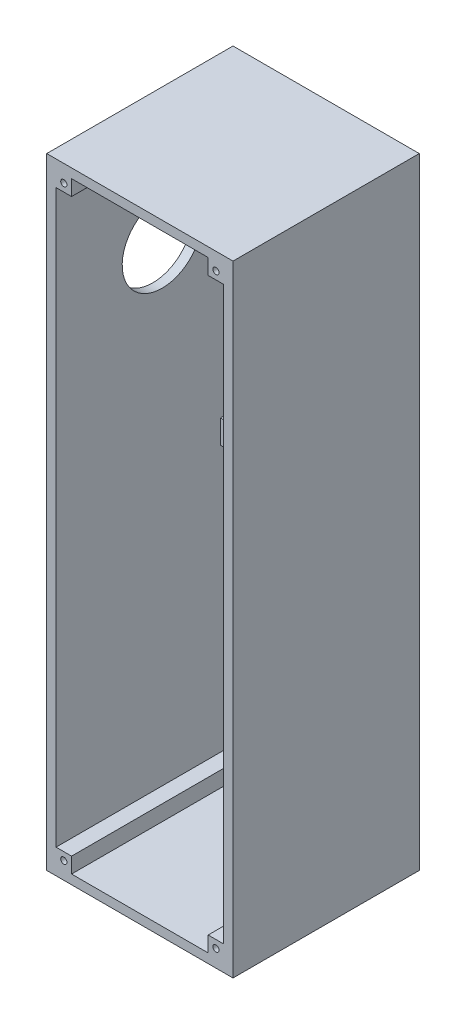
SolidWorks part; units mm, degrees
ref_plane "Płaszczyzna przednia" through (0, 0, 0) normal (0, 0, 1) x (1, 0, 0)
ref_plane "Płaszczyzna górna" through (0, 0, 0) normal (0, 1, 0) x (1, 0, 0)
ref_plane "Płaszczyzna prawa" through (0, 0, 0) normal (1, 0, 0) x (0, 0, -1)
sketch "Szkic1" plane through (0, 0, 0) normal (0, 1, 0) x (1, 0, 0)
  line L1 (0, 0) -> (60, 0)
  line L2 (0, 0) -> (0, 60)
  line L3 (0, 60) -> (60, 60)
  line L4 (60, 0) -> (60, 60)
  dimension "D1" = 60
  dimension "D2" = 60
extrude "Dodanie-wyciągnięcie1" add sketch "Szkic1" along normal blind 200
shell "Skorupa1" thickness 3
sketch "Szkic2" plane through (0, 0, -57) normal (0, 0, 1) x (1, 0, 0)
  line L0 (3, 197) -> (3, 192) construction
  line L1 (3, 197) -> (3, 3) construction
  line L2 (5.5, 194.5) -> (5.5, 197) construction
  line L3 (3, 197) -> (8, 197)
  line L4 (3, 197) -> (3, 192)
  line L5 (3, 192) -> (8, 192)
  line L6 (8, 197) -> (8, 192)
  circle A0 centre (5.5, 194.5) radius 1
  dimension "D3" = 2
  dimension "D1" = 5
  dimension "D2" = 5
extrude "Dodanie-wyciągnięcie5" add sketch "Szkic2" along normal blind 57
sketch "Szkic3" plane through (0, 0, -57) normal (0, 0, 1) x (1, 0, 0)
  line L1 (57, 197) -> (52, 197)
  line L2 (57, 197) -> (57, 192)
  line L3 (57, 192) -> (52, 192)
  line L4 (52, 197) -> (52, 192)
  circle A0 centre (54.5, 194.5) radius 1
  dimension "D2" = 2
  dimension "D1" = 5
extrude "Dodanie-wyciągnięcie6" add sketch "Szkic3" along normal blind 57
sketch "Szkic4" plane through (0, 0, 0) normal (0, 0, 1) x (1, 0, 0)
  line L1 (3, 3) -> (8, 3)
  line L2 (3, 3) -> (3, 8)
  line L3 (3, 8) -> (8, 8)
  line L4 (8, 3) -> (8, 8)
  circle A0 centre (5.5, 5.5) radius 1
  dimension "D2" = 2
  dimension "D1" = 5
extrude "Dodanie-wyciągnięcie7" add sketch "Szkic4" against normal blind 57
sketch "Szkic5" plane through (0, 0, -57) normal (0, 0, 1) x (1, 0, 0)
  line L0 (54.5, 8) -> (54.5, 3) construction
  line L1 (57, 3) -> (52, 3)
  line L2 (57, 3) -> (57, 8)
  line L3 (57, 8) -> (52, 8)
  line L4 (52, 3) -> (52, 8)
  circle A0 centre (54.5, 5.5) radius 1
  dimension "D2" = 2
  dimension "D1" = 5
extrude "Dodanie-wyciągnięcie8" add sketch "Szkic5" along normal blind 57
sketch "Szkic10" plane through (0, 0, 0) normal (-1, 0, 0) x (0, 0, 1)
  line L0 (0, 200) -> (0, 159.72) construction
  line L1 (0, 200) -> (0, 0) construction
  line L2 (0, 159.72) -> (-34.18, 159.72) construction
  circle A0 centre (-34.18, 159.72) radius 12.875
  dimension "D3" = 25.75
  dimension "D1" = 40.28
  dimension "D2" = 34.18
extrude "Wytnij-wyciągnięcie3" cut sketch "Szkic10" against normal blind 3
sketch "Szkic12" plane through (57, 0, 0) normal (-1, 0, 0) x (0, 0, 1)
  line L0 (0, 192) -> (-57, 192) construction
  line L1 (-56.6, 169.76) -> (-25.45, 169.76)
  line L2 (-56.6, 169.76) -> (-56.6, 177.36)
  line L3 (-56.6, 177.36) -> (-25.45, 177.36)
  line L4 (-25.45, 169.76) -> (-25.45, 177.36)
  line L5 (0, 192) -> (0, 8) construction
  line L7 (-56.6, 128.76) -> (-25.45, 128.76)
  line L8 (-56.6, 128.76) -> (-56.6, 121.16)
  line L9 (-56.6, 121.16) -> (-25.45, 121.16)
  line L10 (-25.45, 128.76) -> (-25.45, 121.16)
  line L11 (0, 197) -> (-57, 197) construction
  dimension "D1" = 31.15
  dimension "D2" = 7.6
  dimension "D3" = 27.24
  dimension "D4" = 25.45
  dimension "D5" = 31.15
  dimension "D6" = 7.6
  dimension "D7" = 63.24
  dimension "D8" = 25.45
extrude "Dodanie-wyciągnięcie9" add sketch "Szkic12" along normal blind 26.5
sketch "Szkic13" plane through (30.5, 0, 0) normal (-1, 0, 0) x (0, 0, 1)
  line L0 (-25.45, 177.36) -> (-56.6, 177.36) construction
  line L1 (-25.45, 169.76) -> (-25.45, 177.36) construction
  circle A2 centre (-29.45, 175.36) radius 1.5
  circle A3 centre (-39.1, 175.36) radius 1.5
  dimension "D1" = 3
  dimension "D2" = 4
  dimension "D3" = 3
  dimension "D4" = 13.65
  dimension "D5" = 2
  dimension "D6" = 2
extrude "Wytnij-wyciągnięcie4" cut sketch "Szkic13" against normal blind 5
sketch "Szkic15" plane through (30.5, 0, 0) normal (-1, 0, 0) x (0, 0, 1)
  line L1 (-25.45, 121.16) -> (-25.45, 128.76) construction
  line L3 (-56.6, 121.16) -> (-25.45, 121.16) construction
  circle A0 centre (-29.45, 124.16) radius 1.5
  circle A1 centre (-39.1, 124.16) radius 1.5
  dimension "D1" = 3
  dimension "D2" = 4
  dimension "D3" = 3
  dimension "D5" = 3
  dimension "D6" = 3
  dimension "D4" = 13.65
extrude "Wytnij-wyciągnięcie5" cut sketch "Szkic15" against normal blind 5
sketch "Szkic16" plane through (0, 177.36, 0) normal (0, 1, 0) x (1, 0, 0)
  line L0 (30.5, 25.45) -> (47, 25.45) construction
  line L1 (30.5, 25.45) -> (57, 25.45) construction
  line L2 (57, 25.45) -> (57, 49.45)
  line L3 (47, 25.45) -> (57, 49.45)
  line L4 (47, 25.45) -> (57, 25.45)
  dimension "D1" = 16.5
  dimension "D2" = 24
extrude "Wytnij-wyciągnięcie6" cut sketch "Szkic16" against normal blind 10
sketch "Szkic17" plane through (0, 0, 0) normal (-1, 0, 0) x (0, 0, 1)
  line L0 (-34.18, 171.7348) -> (-34.18, 146.845) construction
  line L2 (-37.93, 172.345) -> (-37.93, 176.655)
  line L3 (-30.43, 172.345) -> (-30.43, 176.655)
  line L4 (-37.93, 172.345) -> (-37.93, 171.7752)
  line L5 (-37.93, 171.7752) -> (-30.43, 171.6944)
  line L6 (-30.43, 171.6944) -> (-30.43, 172.345)
  circle A0 centre (-34.18, 159.72) radius 12.875 construction
  arc A1 (-37.93, 176.655) -> (-30.43, 176.655) centre (-34.18, 176.655) cw
  point P8 (-34.18, 172.345)
  dimension "D1" = 7.5
  dimension "D2" = 4.31
  dimension "D3" = 4.31
extrude "Wytnij-wyciągnięcie7" cut sketch "Szkic17" against normal blind 10
